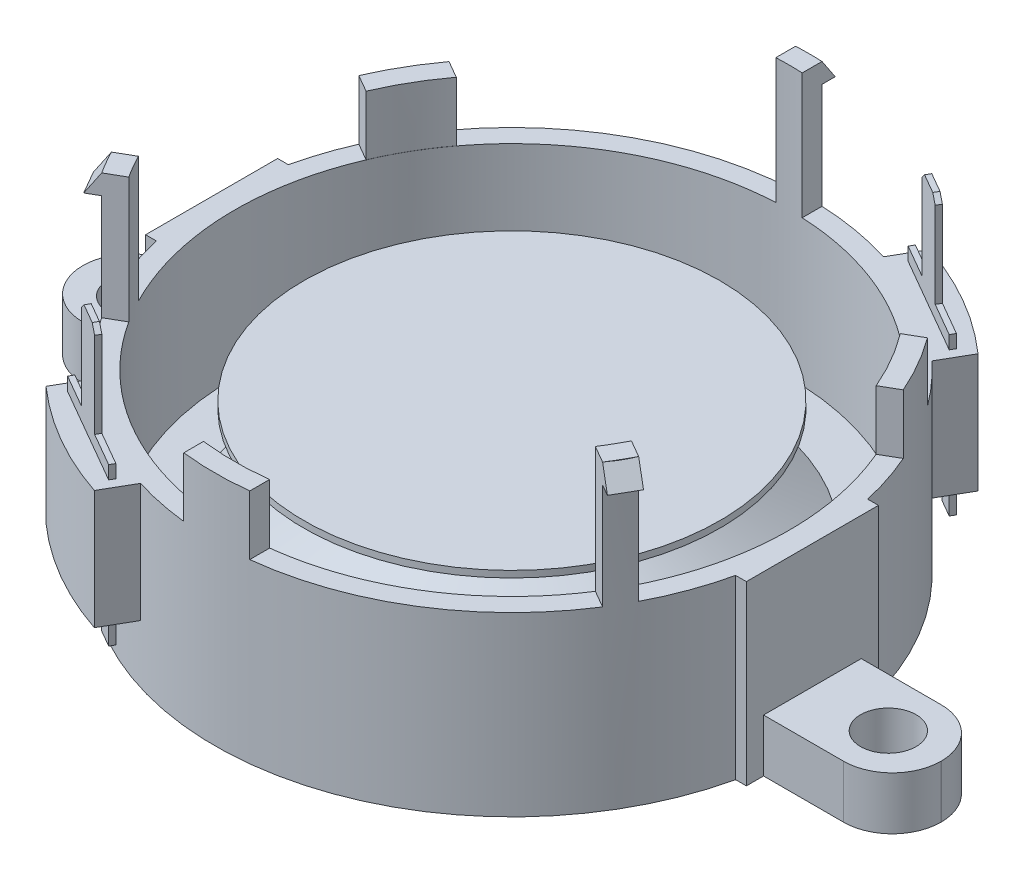
SolidWorks part; units mm, degrees
material "Полиамид ПА-6Б ТУ 6-05-988-87"
ref_plane "Спереди" through (0, 0, 0) normal (0, 0, 1) x (1, 0, 0)
ref_plane "Сверху" through (0, 0, 0) normal (0, 1, 0) x (1, 0, 0)
ref_plane "Справа" through (0, 0, 0) normal (1, 0, 0) x (0, 0, -1)
sketch "Эскиз1" plane through (0, 0, 0) normal (0, 1, 0) x (1, 0, 0)
  circle A0 centre (0, 0) radius 22.5
  dimension "D1" = 45
extrude "Бобышка-Вытянуть1" add sketch "Эскиз1" along normal blind 13.4
sketch "Эскиз2" plane through (0, 0, 0) normal (0, -1, 0) x (1, 0, 0)
  line L0 (0, 22.5) -> (0, 0) construction
  line L1 (22.1937, 3.7) -> (32.5, 3.7)
  line L3 (22.1937, -3.7) -> (32.5, -3.7)
  line L4 (32.5, 3.7) -> (32.5, -3.7)
  line L5 (-22.1937, -3.7) -> (-32.5, -3.7)
  line L7 (-22.1937, 3.7) -> (-32.5, 3.7)
  line L8 (-32.5, -3.7) -> (-32.5, 3.7)
  line L9 (32.5, 0) -> (-32.5, 0) construction
  circle A0 centre (0, 0) radius 22.5 construction
  circle A1 centre (0, 0) radius 22.5
  arc A2 (-22.1937, 3.7) -> (-22.1937, -3.7) centre (0, 0) ccw
  arc A3 (22.1937, -3.7) -> (22.1937, 3.7) centre (0, 0) ccw
  circle A4 centre (28.5, 0) radius 2.1
  circle A5 centre (-28.5, 0) radius 2.1
  dimension "D4" = 4.2
  dimension "D2" = 65
  dimension "D3" = 7.4
  dimension "D5" = 57
  dimension "D1" = 0
extrude "Бобышка-Вытянуть2" add sketch "Эскиз2" against normal blind 4
fillet "Скругление1" radius 3.69 4 edges at (32.5, 2, 3.7) (32.5, 2, -3.7) (-32.5, 2, -3.7) (-32.5, 2, 3.7)
sketch "Эскиз3" plane through (0, 13.4, 0) normal (0, 1, 0) x (1, 0, 0)
  line L0 (-1, 22.4778) -> (-1, 20.9778)
  line L2 (0, 21) -> (0, 22.5) construction
  line L3 (1, 22.4778) -> (1, 20.9778)
  line L4 (19.9663, -10.3729) -> (18.6673, -9.6229)
  line L6 (18.9663, -12.1049) -> (17.6673, -11.3549)
  line L7 (18.1865, -10.5) -> (19.4856, -11.25) construction
  line L8 (-18.9663, -12.1049) -> (-17.6673, -11.3549)
  line L10 (-19.9663, -10.3729) -> (-18.6673, -9.6229)
  line L11 (-18.1865, -10.5) -> (-19.4856, -11.25) construction
  circle A0 centre (0, 0) radius 22.5 construction
  arc A1 (1, 22.4778) -> (-1, 22.4778) centre (0, 0) ccw
  arc A2 (18.9663, -12.1049) -> (19.9663, -10.3729) centre (0, 0) ccw
  arc A3 (-19.9663, -10.3729) -> (-18.9663, -12.1049) centre (0, 0) ccw
  arc A4 (-18.6673, -9.6229) -> (-17.6673, -11.3549) centre (0, 0) ccw
  arc A5 (17.6673, -11.3549) -> (18.6673, -9.6229) centre (0, 0) ccw
  arc A6 (1, 20.9778) -> (-1, 20.9778) centre (0, 0) ccw
  point P26 (0, 0)
  dimension "D1" = 2
  dimension "D2" = 1.5
  dimension "D3" = 3
extrude "Бобышка-Вытянуть3" add sketch "Эскиз3" along normal blind 9.5
sketch "Эскиз7" plane through (-1, 0, 0) normal (-1, 0, 0) x (0, 0, 1)
  line L0 (-22.4778, 22.9) -> (-23.4778, 21.4)
  line L1 (-23.4778, 21.4) -> (-22.4778, 21.4)
  line L2 (-22.4778, 22.9) -> (-22.4778, 13.4) construction
  line L3 (-22.4778, 21.4) -> (-22.4778, 22.9)
  dimension "D1" = 1
  dimension "D2" = 1.5
extrude "Бобышка-Вытянуть5" add sketch "Эскиз7" against normal up to vertex
sketch "Эскиз4" plane through (0, 13.4, 0) normal (0, 1, 0) x (1, 0, 0)
  line L0 (-2.5, -20.8607) -> (-2.5, -22.3607)
  line L1 (0, 0) -> (0, 9.3421) construction
  line L2 (2.5, -20.8607) -> (2.5, -22.3607)
  line L3 (-16.8159, 12.5954) -> (-18.1149, 13.3454)
  line L4 (9.4761, 0) -> (0, 0) construction
  line L5 (-19.3159, 8.2653) -> (-20.6149, 9.0153)
  line L6 (19.3159, 8.2653) -> (20.6149, 9.0153)
  line L7 (16.8159, 12.5954) -> (18.1149, 13.3454)
  arc A0 (-2.5, -22.3607) -> (2.5, -22.3607) centre (0, 0) ccw
  arc A1 (-2.5, -20.8607) -> (2.5, -20.8607) centre (0, 0) ccw
  circle A2 centre (0, 0) radius 22.5 construction
  arc A3 (-18.1149, 13.3454) -> (-20.6149, 9.0153) centre (0, 0) ccw
  arc A4 (-16.8159, 12.5954) -> (-19.3159, 8.2653) centre (0, 0) ccw
  arc A5 (20.6149, 9.0153) -> (18.1149, 13.3454) centre (0, 0) ccw
  arc A6 (19.3159, 8.2653) -> (16.8159, 12.5954) centre (0, 0) ccw
  point P22 (0, 0)
  dimension "D1" = 5
  dimension "D2" = 1.5
  dimension "D3" = 3
extrude "Бобышка-Вытянуть4" add sketch "Эскиз4" along normal blind 4.5
sketch "Эскиз5" plane through (0, 13.4, 0) normal (0, 1, 0) x (1, 0, 0)
  circle A0 centre (0, 0) radius 21.0016
  dimension "D1" = 42.0032
extrude "Вырез-Вытянуть1" cut sketch "Эскиз5" against normal blind 11
sketch "Эскиз6" plane through (0, 0, 0) normal (0, -1, 0) x (-1, 0, 0)
  circle A0 centre (0, 0) radius 8
  dimension "D1" = 16
extrude "Вырез-Вытянуть2" cut sketch "Эскиз6" against normal blind 3
pattern_circular "Круговой массив1" count 3 over 360 about axis through (0, 0, 0) along (0, 1, 0) of "Бобышка-Вытянуть5"
sketch "Эскиз8" plane through (0, 13.4, 0) normal (0, 1, 0) x (1, 0, 0)
  line L0 (7.9173, 23.7132) -> (6.6386, 21.4984)
  line L1 (0, 0) -> (13.8032, 23.9079) construction
  line L2 (16.5776, 18.7132) -> (15.2988, 16.4984)
  line L3 (0, 14.8355) -> (0, 0) construction
  line L4 (14.3383, 0) -> (0, 0) construction
  line L5 (-7.9173, -23.7132) -> (-6.6386, -21.4984)
  line L6 (-16.5776, -18.7132) -> (-15.2988, -16.4984)
  circle A0 centre (0, 0) radius 22.5 construction
  arc A1 (-15.2988, -16.4984) -> (-6.6386, -21.4984) centre (0, 0) ccw
  arc A2 (-16.5776, -18.7132) -> (-7.9173, -23.7132) centre (0, 0) ccw
  arc A3 (15.2988, 16.4984) -> (6.6386, 21.4984) centre (0, 0) ccw
  arc A4 (16.5776, 18.7132) -> (7.9173, 23.7132) centre (0, 0) ccw
  point P20 (0, 0)
  dimension "D1" = 50
  dimension "D2" = 10
  dimension "D3" = 30
  dimension "D4" = 2
extrude "Бобышка-Вытянуть6" add sketch "Эскиз8" against normal blind 9
sketch "Эскиз9" plane through (0, 13.4, 0) normal (0, 1, 0) x (1, 0, 0)
  line L0 (8.0694, 22.4766) -> (7.8694, 22.1302)
  line L1 (7.8694, 22.1302) -> (15.2306, 17.8802)
  line L2 (15.2306, 17.8802) -> (15.4306, 18.2266)
  line L3 (15.4306, 18.2266) -> (8.0694, 22.4766)
  line L4 (0, 0) -> (12.5, 21.6506) construction
  line L5 (7.9173, 23.7132) -> (6.6386, 21.4984) construction
  line L6 (0, 0) -> (11.2177, -6.4765) construction
  line L7 (-8.0694, -22.4766) -> (-15.4306, -18.2266)
  line L8 (-7.8694, -22.1302) -> (-8.0694, -22.4766)
  line L9 (-15.2306, -17.8802) -> (-7.8694, -22.1302)
  line L10 (-15.4306, -18.2266) -> (-15.2306, -17.8802)
  arc A0 (16.5776, 18.7132) -> (7.9173, 23.7132) centre (0, 0) ccw construction
  dimension "D1" = 8.5
  dimension "D2" = 0.4
  dimension "D3" = 47
extrude "Бобышка-Вытянуть7" add sketch "Эскиз9" along normal blind 1
sketch "Эскиз10" plane through (0, 14.4, 0) normal (0, 1, 0) x (1, 0, 0)
  line L0 (10.5809, 21.0266) -> (10.3809, 20.6802)
  line L1 (15.4306, 18.2266) -> (8.0694, 22.4766) construction
  line L2 (7.8694, 22.1302) -> (15.2306, 17.8802) construction
  line L3 (10.3809, 20.6802) -> (12.7191, 19.3302)
  line L4 (12.7191, 19.3302) -> (12.9191, 19.6766)
  line L5 (12.9191, 19.6766) -> (10.5809, 21.0266)
  line L6 (0, 0) -> (12.5, 21.6506) construction
  line L7 (0, 0) -> (11.9851, -6.9196) construction
  line L8 (-10.5809, -21.0266) -> (-12.9191, -19.6766)
  line L9 (-10.3809, -20.6802) -> (-10.5809, -21.0266)
  line L10 (-12.7191, -19.3302) -> (-10.3809, -20.6802)
  line L11 (-12.9191, -19.6766) -> (-12.7191, -19.3302)
  arc A0 (16.5776, 18.7132) -> (7.9173, 23.7132) centre (0, 0) ccw construction
  dimension "D1" = 2.7
extrude "Бобышка-Вытянуть8" add sketch "Эскиз10" along normal blind 7
chamfer "Фаска1" distance 0.5 angle 45 4 edges at (10.4809, 21.4, -20.8534) (12.8191, 21.4, -19.5034) (-12.8191, 21.4, 19.5034) (-10.4809, 21.4, 20.8534)
sketch "Эскиз11" plane through (0, 0, 0) normal (1, 0, 0) x (0, 0, -1)
  line L0 (-0.01, 0) -> (-0.01, 22.8012) construction
  line L1 (20.5, 2.4) -> (17.5, 2.4)
  line L2 (17.5, 2.4) -> (4.99, 9.6227)
  line L3 (4.99, 9.6227) -> (4.99, 10.9)
  line L4 (4.99, 10.9) -> (15.74, 10.9)
  line L5 (15.74, 10.9) -> (15.74, 11.4)
  line L6 (15.74, 11.4) -> (-0.01, 11.4)
  line L7 (8, 2.4) -> (-8, 2.4) construction
  line L8 (20.5, 2.4) -> (20.5, 1.9)
  line L9 (20.5, 1.9) -> (17.366, 1.9)
  line L10 (17.366, 1.9) -> (4.49, 9.334)
  line L11 (4.49, 9.334) -> (4.49, 10.9)
  line L12 (4.49, 10.9) -> (-0.01, 10.9)
  line L13 (-0.01, 10.9) -> (-0.01, 11.4)
  line L15 (16.4984, 13.4) -> (13.3454, 13.4) construction
  line L16 (22.5, 0) -> (22.5, 21.4) construction
  dimension "D1" = 0.5
  dimension "D2" = 0.5
  dimension "D3" = 3
  dimension "D4" = 2
  dimension "D5" = 0.5
  dimension "D6" = 0.5
  dimension "D7" = 2
  dimension "D8" = 150
  dimension "D9" = 5
  dimension "D10" = 31.5
revolve "Повернуть1" add sketch "Эскиз11" angle 360 about L0
sketch "Эскиз12" plane through (0, 4, 0) normal (0, 1, 0) x (1, 0, 0)
  circle A0 centre (0, 0) radius 22.5
  circle A1 centre (0, 0) radius 34
  arc A2 (6.6386, 21.4984) -> (1, 22.4778) centre (0, 0) ccw construction
  dimension "D1" = 68
extrude "Вырез-Вытянуть3" [suppressed] cut sketch "Эскиз12" against normal up to vertex
sketch "Эскиз13" plane through (0, 0, 0) normal (0, -1, 0) x (1, 0, 0)
  circle A0 centre (0, 0) radius 9.5
  dimension "D1" = 19
extrude "Вырез-Вытянуть4" cut sketch "Эскиз13" against normal blind 2
sketch "Эскиз15" plane through (0, 0, 0) normal (0, -1, 0) x (1, 0, 0)
  line L0 (0, 0) -> (-13.2112, 0) construction
  line L1 (-21.9374, 5) -> (-22.75, 5)
  line L2 (-21.9374, -5) -> (-22.75, -5)
  line L3 (-22.75, 5) -> (-22.75, -5)
  line L4 (0, 0) -> (0, 11.1502) construction
  line L5 (22.75, 5) -> (22.75, -5)
  line L6 (21.9374, -5) -> (22.75, -5)
  line L7 (21.9374, 5) -> (22.75, 5)
  arc A0 (22.1937, 3.7) -> (-22.1937, 3.7) centre (0, 0) ccw construction
  arc A1 (-21.9374, -5) -> (-21.9374, 5) centre (0, 0) cw
  arc A2 (21.9374, -5) -> (21.9374, 5) centre (0, 0) ccw
  dimension "D2" = 45.5
  dimension "D1" = 10
extrude "Бобышка-Вытянуть10" add sketch "Эскиз15" against normal up to surface (13.4 mm away) up to face at (-15.9013, 13.4, -9.1806)
ref_plane "Плоскость1" through (0, 0, 0) normal (0.5, 0, -0.866) x (-0.866, 0, -0.5)
sketch "Эскиз18" plane through (11.75, 0, -20.3516) normal (0.5, 0, -0.866) x (-0.866, 0, -0.5)
  line L0 (0, 13.4) -> (0, 16.3783) construction
  line L1 (-4.25, 14.4) -> (-2.75, 14.4)
  line L2 (-4.25, 14.4) -> (-4.25, 2.5)
  line L3 (-4.25, 2.5) -> (-2.75, 2.5)
  line L4 (-2.75, 14.4) -> (-2.75, 2.5)
  line L5 (-4.25, 13.4) -> (4.25, 13.4) construction
  line L6 (2.75, 14.4) -> (2.75, 2.5)
  line L7 (4.25, 2.5) -> (2.75, 2.5)
  line L8 (4.25, 14.4) -> (4.25, 2.5)
  line L9 (4.25, 14.4) -> (2.75, 14.4)
  line L10 (-16.4984, 0) -> (22.5, 0) construction
  dimension "D1" = 1.5
  dimension "D2" = 2.5
extrude "Бобышка-Вытянуть11" add sketch "Эскиз18" against normal up to surface (0.4 mm away) up to face at (11.55, 16.9, -20.0052)
mirror "Зеркальное отражение1" about plane through (0, 0, 0) normal (0.5, 0, -0.866) of "Бобышка-Вытянуть11"
